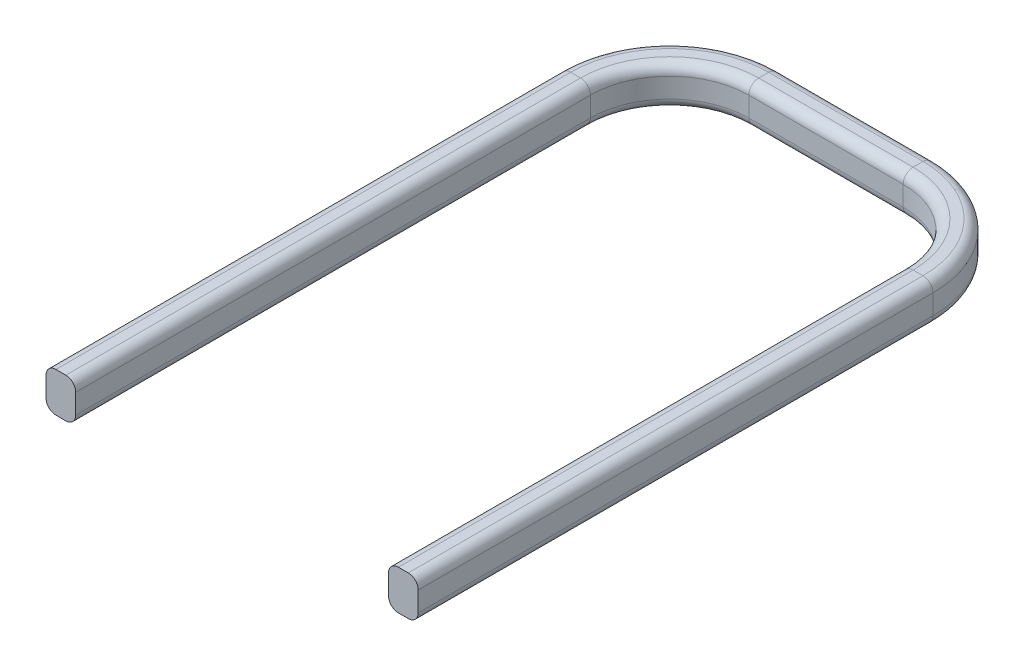
SolidWorks part; units mm, degrees
ref_plane "Front Plane" through (0, 0, 0) normal (0, 0, 1) x (1, 0, 0)
ref_plane "Top Plane" through (0, 0, 0) normal (0, 1, 0) x (1, 0, 0)
ref_plane "Right Plane" through (0, 0, 0) normal (1, 0, 0) x (0, 0, -1)
sketch "Sketch1" plane through (0, 0, 0) normal (0, 1, 0) x (1, 0, 0)
  line L0 (-3.95, 0) -> (-3.95, 13)
  line L1 (-1.95, 15) -> (1.95, 15)
  line L2 (3.95, 13) -> (3.95, 0)
  arc A0 (1.95, 15) -> (3.95, 13) centre (1.95, 13) cw
  arc A1 (-3.95, 13) -> (-1.95, 15) centre (-1.95, 13) cw
  point P4 (-3.95, 0)
  point P5 (3.1976, 0)
  point P7 (0, 0)
  point P8 (0, 15)
  point P13 (0, 0)
  dimension "D3" = 2
  dimension "D1" = 3.95
  dimension "D2" = 15
sketch "Sketch2" plane through (0, 0, 0) normal (0, 0, 1) x (1, 0, 0)
  line L0 (-1.95, 0) -> (-3.95, 0) construction
  line L1 (-3.95, 0) -> (-4.7, 0)
  line L2 (-3.95, 0) -> (-3.95, 1)
  line L3 (-3.95, 1) -> (-4.7, 1)
  line L4 (-4.7, 0) -> (-4.7, 1)
  point P6 (-3.95, 0)
  dimension "D1" = 1
  dimension "D2" = 0.75
sweep "Sweep1" add profiles "Sketch2" path "Sketch1"
fillet "Fillet1" radius 0.25 20 edges at (4.7, 0, -6.5) (3.8945, 0, -14.9445) (0, 0, -15.75) (-3.8945, 0, -14.9445) (3.95, 0, -6.5) (3.3642, 0, -14.4142) (0, 0, -15) (-3.3642, 0, -14.4142) (3.95, 1, -6.5) (3.3642, 1, -14.4142) (0, 1, -15) (-3.3642, 1, -14.4142) (4.7, 1, -6.5) (3.8945, 1, -14.9445) (0, 1, -15.75) (-3.8945, 1, -14.9445) (-4.7, 0, -6.5) (-3.95, 0, -6.5) (-3.95, 1, -6.5) (-4.7, 1, -6.5)
